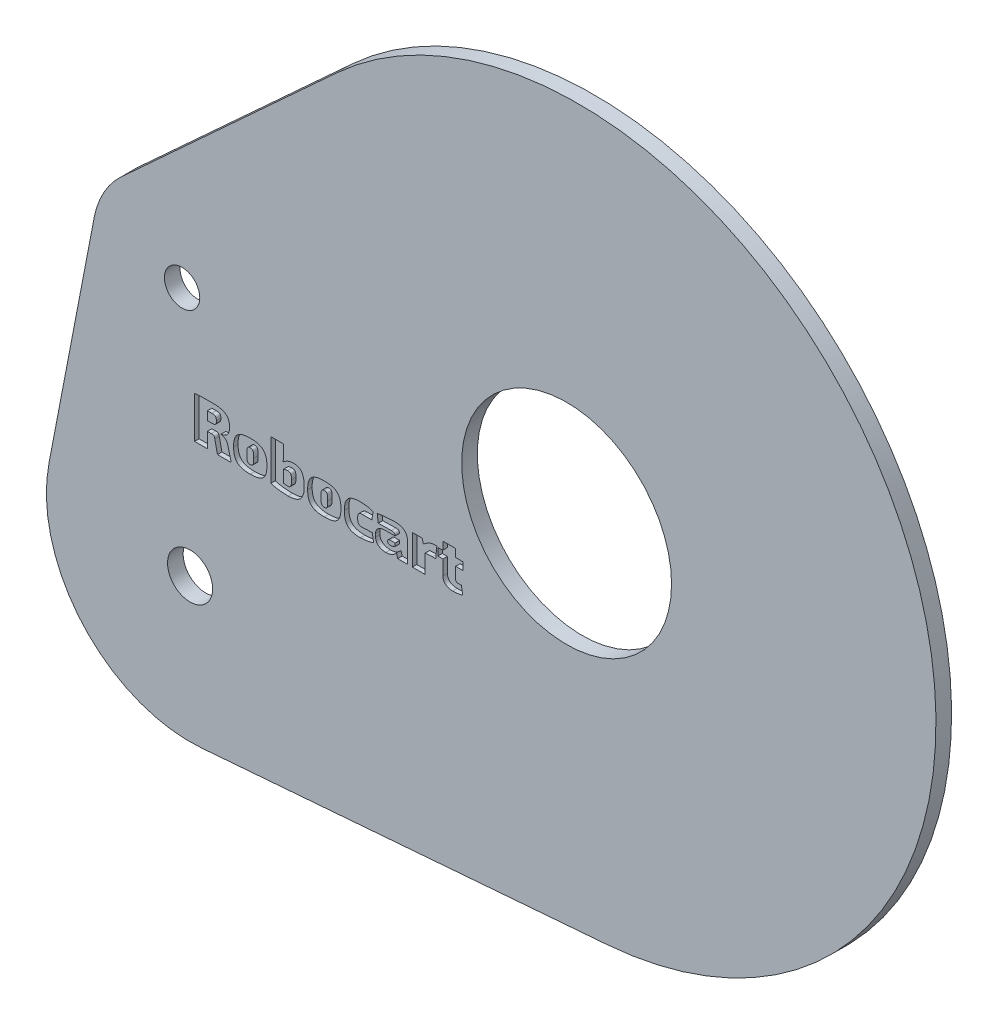
SolidWorks part; units mm, degrees
ref_plane "Front Plane" through (0, 0, 0) normal (0, 0, 1) x (1, 0, 0)
ref_plane "Top Plane" through (0, 0, 0) normal (0, 1, 0) x (1, 0, 0)
ref_plane "Right Plane" through (0, 0, 0) normal (1, 0, 0) x (0, 0, -1)
sketch "Sketch1" plane through (0, 0, 0) normal (0, 0, 1) x (1, 0, 0)
  line L0 (0, 0) -> (112.7125, 0) construction
  line L1 (-17.211, 18.7512) -> (43.9638, 74.9011)
  line L2 (-17.211, -18.7512) -> (43.9638, -74.9011)
  arc A0 (43.9638, -74.9011) -> (43.9638, 74.9011) centre (112.7125, 0) ccw
  arc A1 (-17.211, 18.7512) -> (-17.211, -18.7512) centre (0, 0) ccw
  circle A2 centre (0, 0) radius 5.0254
  circle A3 centre (112.7125, 0) radius 3.175
  circle A4 centre (0, 0) radius 12.7525 construction
  circle A5 centre (112.7125, 0) radius 88.9689 construction
  dimension "D1" = 12.7
  dimension "D3" = 12.7
  dimension "D4" = 6.35
  dimension "D5" = 10.0508
  dimension "D6" = 25.5049
  dimension "D8" = 112.7125
  dimension "D7" = 177.9378
extrude "Boss-Extrude1" add sketch "Sketch1" along normal blind 4.445
sketch "Sketch3" [suppressed] plane through (0, 0, 0) normal (0, 0, 1) x (1, 0, 0)
  circle A0 centre (49.3634, -28.5) radius 5.715
  dimension "D1" = 11.43
  dimension "D2" = 49.3634
  dimension "D3" = 28.5
extrude "Cut-Extrude4" [suppressed] cut sketch "Sketch3" along normal through all
sketch "Sketch2" plane through (0, 0, 0) normal (0, 0, 1) x (1, 0, 0)
  line L0 (-24.9954, 4.8019) -> (-37.8559, -62.1404)
  line L1 (5.5388, -110.5837) -> (120.8341, -101.344)
  line L2 (-17.211, -18.7512) -> (43.9638, -74.9011) construction
  line L3 (-17.211, -18.7512) -> (43.9638, -74.9011)
  arc A0 (-37.8559, -62.1404) -> (5.5388, -110.5837) centre (2.2745, -69.85) ccw
  arc A1 (-17.211, 18.7512) -> (-17.211, -18.7512) centre (0, 0) ccw construction
  arc A2 (43.9638, -74.9011) -> (43.9638, 74.9011) centre (112.7125, 0) ccw construction
  arc A3 (-24.9954, 4.8019) -> (-17.211, -18.7512) centre (0, 0) ccw
  arc A4 (43.9638, -74.9011) -> (120.8341, -101.344) centre (112.7125, 0) ccw
  circle A5 centre (2.2745, -69.85) radius 6.4135
  circle A6 centre (2.2745, -69.85) radius 28.1642 construction
  dimension "D1" = 12.7
  dimension "D2" = 12.827
  dimension "D3" = 56.3285
  dimension "D4" = 69.85
  dimension "D5" = 2.2745
extrude "Boss-Extrude2" add sketch "Sketch2" along normal up to surface (4.445 mm away) up to face at (5.0254, 0, 4.445)
sketch "Sketch4" plane through (0, 0, 0) normal (0, 0, 1) x (1, 0, 0)
  line L1 (101.2058, 98.9276) -> (-152.7942, 98.9276) construction
  line L2 (101.2058, 98.9276) -> (101.2058, -116.9724) construction
  line L3 (101.2058, -116.9724) -> (-152.7942, -116.9724) construction
  line L4 (-152.7942, 98.9276) -> (-152.7942, -116.9724) construction
  dimension "D1" = 254
  dimension "D2" = 215.9
sketch "Sketch5" plane through (0, 0, 4.445) normal (0, 0, 1) x (1, 0, 0)
  line L0 (2.6035, -36.0675) -> (85.1535, -36.0675) construction
  line L1 (71.8753, 217.5354) -> (771.2087, 217.5354) construction
  text T0 "Robocart" font "Exo 2.0 Black" height in points 48
  dimension "D1" = 82.55
extrude "Cut-Extrude5" cut sketch "Sketch5" against normal blind 1.27
sketch "Sketch6" [suppressed] plane through (0, 0, 0) normal (0, 0, -1) x (-1, 0, 0)
  line L1 (-102.007, 50.1084) -> (-88.5041, 50.1084)
  line L2 (-102.007, 50.1084) -> (-102.007, 43.8891)
  line L3 (-102.007, 43.8891) -> (-88.5041, 43.8891)
  line L4 (-88.5041, 50.1084) -> (-88.5041, 43.8891)
extrude "Cut-Extrude6" [suppressed] cut sketch "Sketch6" against normal blind 2.54
sketch "Sketch7" plane through (0, 0, 0) normal (0, 0, 1) x (1, 0, 0)
  line L0 (109.3449, -3.3676) -> (112.7125, 0) construction
  line L1 (112.7125, 0) -> (105.7454, 0) construction
  circle A0 centre (109.3449, -3.3676) radius 29.845
  dimension "D1" = 59.69
  dimension "D2" = 45
  dimension "D3" = 4.7625
extrude "Cut-Extrude8" cut sketch "Sketch7" along normal through all
